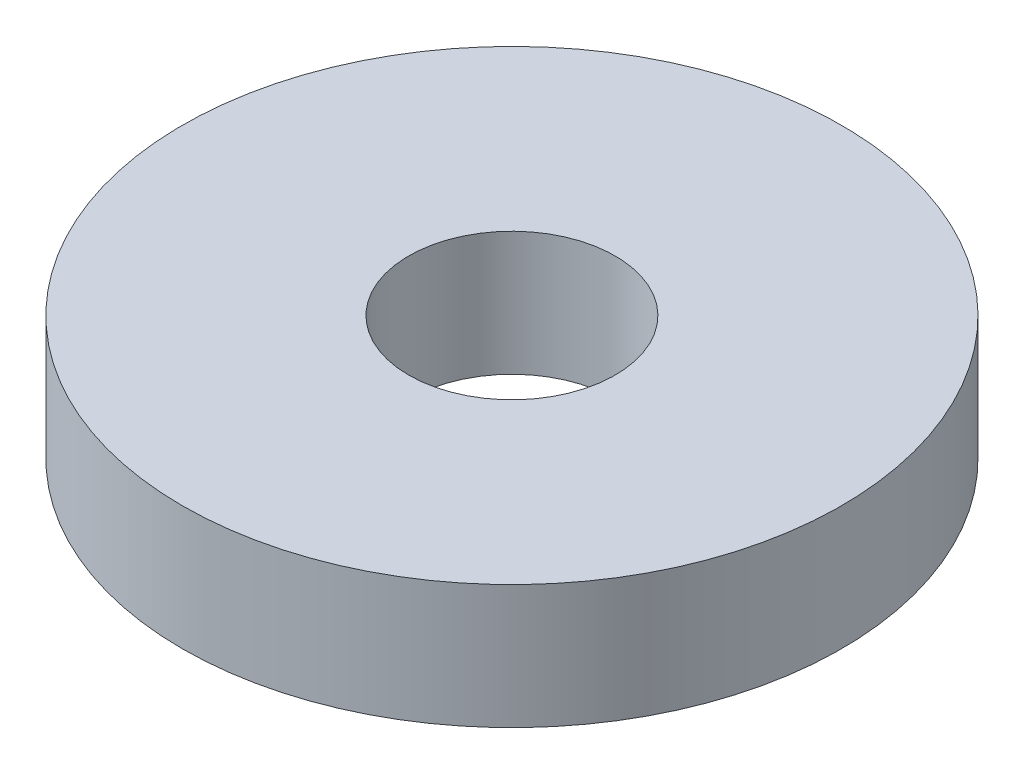
SolidWorks part; units mm, degrees
material "Acrylic (Medium-high impact)"
ref_plane "Front Plane" through (0, 0, 0) normal (0, 0, 1) x (1, 0, 0)
ref_plane "Top Plane" through (0, 0, 0) normal (0, 1, 0) x (1, 0, 0)
ref_plane "Right Plane" through (0, 0, 0) normal (1, 0, 0) x (0, 0, -1)
sketch "Sketch2" plane through (0, 0, 0) normal (0, 1, 0) x (1, 0, 0)
  circle A0 centre (0, 0) radius 7.98
  circle A1 centre (0, 0) radius 2.5
  dimension "D1" = 15.96
  dimension "D2" = 5
extrude "Boss-Extrude1" add sketch "Sketch2" along normal blind 3
